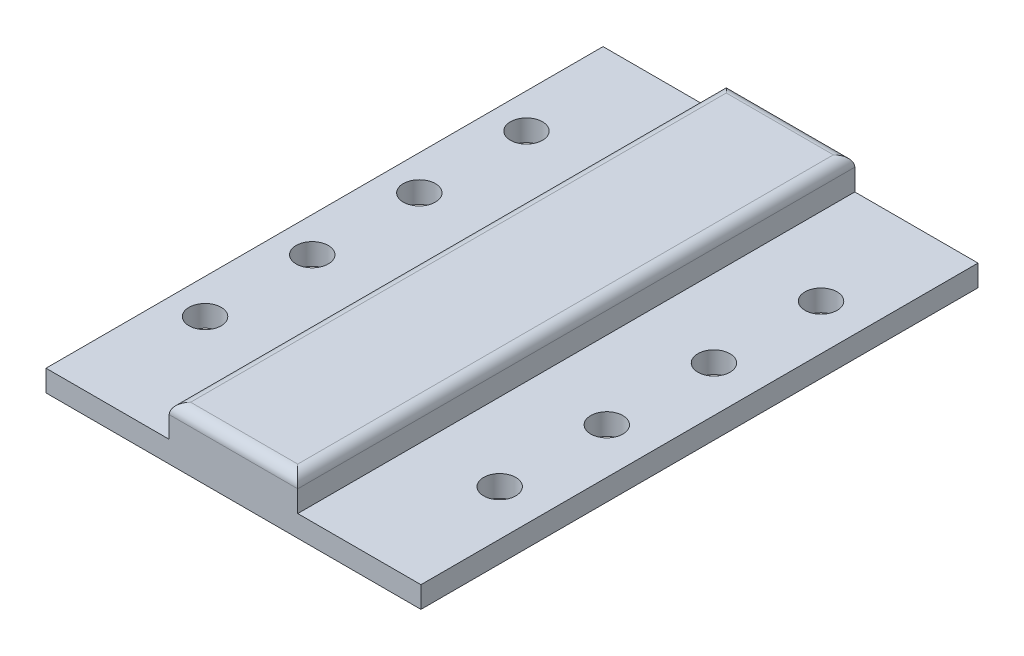
SolidWorks part; units mm, degrees
ref_plane "Спереди" through (0, 0, 0) normal (0, 0, 1) x (1, 0, 0)
ref_plane "Сверху" through (0, 0, 0) normal (0, 1, 0) x (1, 0, 0)
ref_plane "Справа" through (0, 0, 0) normal (1, 0, 0) x (0, 0, -1)
sketch "Эскиз1" plane through (0, 0, 0) normal (0, 1, 0) x (1, 0, 0)
  line L0 (17.5, -26) -> (-17.5, -26)
  line L1 (17.5, -26) -> (17.5, 26)
  line L2 (17.5, 26) -> (-17.5, 26)
  line L3 (-17.5, -26) -> (-17.5, 26)
extrude "Бобышка-Вытянуть1" add sketch "Эскиз1" along normal blind 2
sketch "Эскиз2" plane through (0, 0, 0) normal (0, 0, 1) x (1, 0, 0)
  line L0 (-17.5, 2) -> (17.5, 2) construction
  line L1 (-6, 2) -> (6, 2)
  line L2 (-6, 2) -> (-6, 5)
  line L3 (-6, 5) -> (6, 5)
  line L4 (6, 2) -> (6, 5)
  line L7 (0, 5) -> (0, 2) construction
  line L8 (0, 0) -> (0, 2) construction
  line L9 (-17.5, 0) -> (17.5, 0) construction
  dimension "D1" = 0
  dimension "D2" = 12
  dimension "D3" = 3
extrude "Бобышка-Вытянуть2" add sketch "Эскиз2" along normal up to surface and the other way up to surface up to face at (0, 1, 26) other way up to face at (0, 1, -26)
sketch "Эскиз3" plane through (0, 2, 0) normal (0, 1, 0) x (1, 0, 0)
  line L0 (0, 26) -> (0, -26) construction
  line L5 (-6, 26) -> (6, 26) construction
  line L6 (-6, -26) -> (6, -26) construction
  circle A0 centre (13.25, 15.6) radius 1.5
  circle A1 centre (-14.25, 15.6) radius 1.5
  circle A2 centre (-14.25, 5.6) radius 1.5
  circle A3 centre (13.25, 5.6) radius 1.5
  circle A4 centre (-14.25, -4.4) radius 1.5
  circle A5 centre (13.25, -4.4) radius 1.5
  circle A6 centre (-14.25, -14.4) radius 1.5
  circle A7 centre (13.25, -14.4) radius 1.5
  dimension "D1" = 4
extrude "Вырез-Вытянуть1" cut sketch "Эскиз3" against normal blind 10
fillet "Скругление1" radius 1 4 edges at (0, 5, 26) (0, 5, -26) (-6, 5, 0) (6, 5, 0)
sketch "Эскиз4" plane through (0, 2, 0) normal (0, 1, 0) x (1, 0, 0)
  line L0 (-17.5, 0) -> (17.5, 0) construction
  line L1 (-17.5, 26) -> (-17.5, -26) construction
  line L2 (17.5, -26) -> (17.5, 26) construction
  line L3 (-14.25, 15.6) -> (13.25, 15.6) construction
  line L4 (13.25, 15.6) -> (13.25, 5.6) construction
  line L5 (13.25, 5.6) -> (-14.25, 5.6) construction
  line L6 (-14.25, 5.6) -> (-14.25, -4.4) construction
  line L7 (-14.25, -4.4) -> (13.25, -4.4) construction
  line L8 (13.25, -4.4) -> (13.25, -14.4) construction
  line L9 (13.25, -14.4) -> (-14.25, -14.4) construction
  line L10 (-6, 26) -> (-17.5, 26) construction
  line L12 (-17.5, -26) -> (-6, -26) construction
  dimension "D1" = 10.4
  dimension "D2" = 11.6
